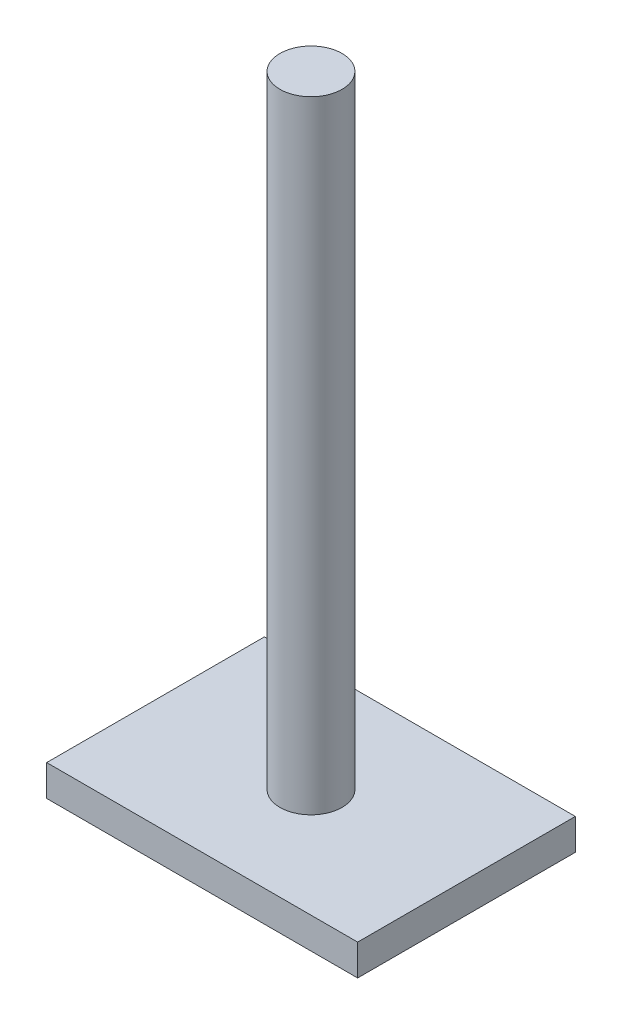
SolidWorks part; units mm, degrees
ref_plane "Front Plane" through (0, 0, 0) normal (0, 0, 1) x (1, 0, 0)
ref_plane "Top Plane" through (0, 0, 0) normal (0, 1, 0) x (1, 0, 0)
ref_plane "Right Plane" through (0, 0, 0) normal (1, 0, 0) x (0, 0, -1)
sketch "Sketch1" plane through (0, 0, 0) normal (0, 1, 0) x (1, 0, 0)
  line L1 (-2.5, 1.75) -> (2.5, 1.75)
  line L2 (-2.5, 1.75) -> (-2.5, -1.75)
  line L3 (-2.5, -1.75) -> (2.5, -1.75)
  line L4 (2.5, 1.75) -> (2.5, -1.75)
  line L5 (-2.5, 1.75) -> (2.5, -1.75) construction
  line L6 (-2.5, -1.75) -> (2.5, 1.75) construction
  point P0 (0, 0)
extrude "Boss-Extrude1" add sketch "Sketch1" along normal blind 0.5
sketch "Sketch2" plane through (0, 0.5, 0) normal (0, 1, 0) x (1, 0, 0)
  circle A0 centre (0, 0) radius 0.4997
extrude "Boss-Extrude2" add sketch "Sketch2" along normal blind 10
